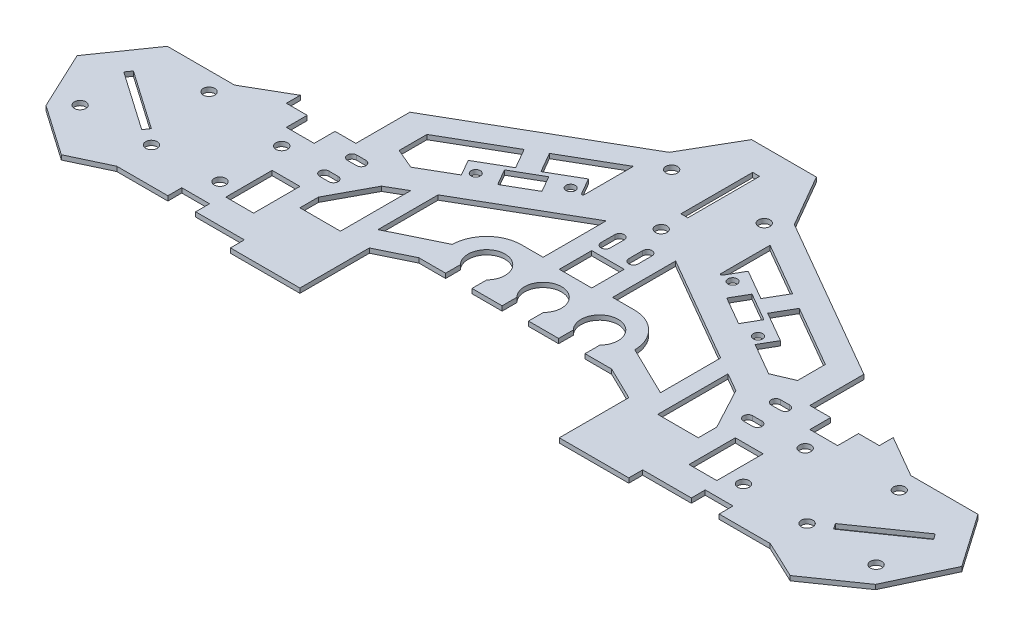
SolidWorks part; units mm, degrees
material "Thornel Mat VMA"
ref_plane "Alzado" through (0, 0, 0) normal (0, 0, 1) x (1, 0, 0)
ref_plane "Planta" through (0, 0, 0) normal (0, 1, 0) x (1, 0, 0)
ref_plane "Vista lateral" through (0, 0, 0) normal (1, 0, 0) x (0, 0, -1)
sketch "Croquis1" plane through (0, 0, 0) normal (0, 1, 0) x (1, 0, 0)
  line L0 (0, 0) -> (0, 58) construction
  line L1 (-7, 58) -> (7, 58)
  line L2 (7, 58) -> (13.5, 46.7417)
  line L3 (13.5, 46.7417) -> (49.007, 26.2417)
  line L4 (49.007, 26.2417) -> (49.007, 14.5814)
  line L5 (49.007, 14.5814) -> (53.507, 14.5814)
  line L6 (53.507, 14.5814) -> (53.507, 10.0814)
  line L7 (53.507, 10.0814) -> (59.507, 10.0814)
  line L8 (59.507, 10.0814) -> (59.507, 14.5814)
  line L9 (59.507, 14.5814) -> (64.007, 14.5814)
  line L10 (64.007, 14.5814) -> (64.007, 17.5814)
  line L11 (64.007, 17.5814) -> (73.007, 12.3853)
  line L12 (73.007, 12.3853) -> (87.507, 12.3853)
  line L13 (87.507, 12.3853) -> (95.5, 0.8912)
  line L14 (95.5, 0.8912) -> (89.5424, -11.7779)
  line L15 (89.5424, -11.7779) -> (78.6824, -19.3299)
  line L16 (78.6824, -19.3299) -> (70.538, -15.5)
  line L17 (70.538, -15.5) -> (59.507, -15.5)
  line L18 (59.507, -15.5) -> (59.507, -12.5)
  line L19 (59.507, -12.5) -> (53.507, -12.5)
  line L20 (53.507, -12.5) -> (53.507, -15.5)
  line L21 (53.507, -15.5) -> (43, -15.5)
  line L22 (43, -15.5) -> (43, -18.5)
  line L23 (43, -18.5) -> (28, -18.5)
  line L24 (28, -18.5) -> (28, -3.5)
  line L25 (28, -3.5) -> (20.8063, 0)
  line L26 (20.8063, 0) -> (15.05, 0)
  line L27 (15.05, 0) -> (15.05, 3.1933)
  line L28 (-2.85, 0) -> (-2.85, 3.1933)
  line L29 (9.35, 0) -> (9.35, 3.1933)
  line L30 (9.35, 0) -> (2.85, 0)
  line L31 (2.85, 0) -> (2.85, 3.1933)
  line L32 (-9.35, 0) -> (-2.85, 0)
  line L33 (-9.35, 0) -> (-9.35, 3.1933)
  line L34 (-15.05, 0) -> (-15.05, 3.1933)
  line L35 (-20.8063, 0) -> (-15.05, 0)
  line L36 (-28, -3.5) -> (-20.8063, 0)
  line L37 (-28, -18.5) -> (-28, -3.5)
  line L38 (-43, -18.5) -> (-28, -18.5)
  line L39 (-43, -15.5) -> (-43, -18.5)
  line L40 (-53.507, -15.5) -> (-43, -15.5)
  line L41 (-53.507, -12.5) -> (-53.507, -15.5)
  line L42 (-59.507, -12.5) -> (-53.507, -12.5)
  line L43 (-59.507, -15.5) -> (-59.507, -12.5)
  line L44 (-70.538, -15.5) -> (-59.507, -15.5)
  line L45 (-78.6824, -19.3299) -> (-70.538, -15.5)
  line L46 (-89.5424, -11.7779) -> (-78.6824, -19.3299)
  line L47 (-95.5, 0.8912) -> (-89.5424, -11.7779)
  line L48 (-87.507, 12.3853) -> (-95.5, 0.8912)
  line L49 (-73.007, 12.3853) -> (-87.507, 12.3853)
  line L50 (-64.007, 17.5814) -> (-73.007, 12.3853)
  line L51 (-64.007, 14.5814) -> (-64.007, 17.5814)
  line L52 (-59.507, 14.5814) -> (-64.007, 14.5814)
  line L53 (-59.507, 10.0814) -> (-59.507, 14.5814)
  line L54 (-53.507, 10.0814) -> (-59.507, 10.0814)
  line L55 (-53.507, 14.5814) -> (-53.507, 10.0814)
  line L56 (-49.007, 14.5814) -> (-53.507, 14.5814)
  line L57 (-49.007, 26.2417) -> (-49.007, 14.5814)
  line L58 (-13.5, 46.7417) -> (-49.007, 26.2417)
  line L59 (-7, 58) -> (-13.5, 46.7417)
  arc A0 (15.05, 3.1933) -> (9.35, 3.1933) centre (12.2, 6) ccw
  arc A1 (2.85, 3.1933) -> (-2.85, 3.1933) centre (0, 6) ccw
  arc A3 (-15.05, 3.1933) -> (-9.35, 3.1933) centre (-12.2, 6) cw
  point P54 (0, 10)
  dimension "D26" = 120
  dimension "D29" = 14
  dimension "D13" = 8
  dimension "D1" = 58
  dimension "D2" = 7
  dimension "D3" = 120
  dimension "D4" = 120
  dimension "D5" = 6
  dimension "D6" = 15
  dimension "D7" = 4.5
  dimension "D8" = 3
  dimension "D9" = 14.5
  dimension "D10" = 9
  dimension "D11" = 41
  dimension "D12" = 13
  dimension "D14" = 10
  dimension "D15" = 2.85
  dimension "D16" = 5.7
  dimension "D17" = 6.5
  dimension "D18" = 95.5
  dimension "D19" = 3
  dimension "D20" = 18.5
  dimension "D21" = 28
  dimension "D22" = 15
  dimension "D23" = 8
  dimension "D24" = 120
  dimension "D25" = 150
  dimension "D27" = 3
  dimension "D28" = 15
  dimension "D30" = 9
extrude "Saliente-Extruir1" add sketch "Croquis1" along normal blind 1
sketch "Croquis2" plane through (0, 1, 0) normal (0, 1, 0) x (1, 0, 0)
  line L0 (0, 10) -> (0, 58) construction
  line L1 (7, 58) -> (-7, 58) construction
  line L2 (3, 25.5) -> (3, 22.5) construction
  line L3 (-3.5, 20) -> (3.5, 20)
  line L4 (-3.5, 20) -> (-3.5, 13)
  line L5 (-3.5, 13) -> (3.5, 13)
  line L6 (3.5, 20) -> (3.5, 13)
  line L7 (-3.5, 20) -> (3.5, 13) construction
  line L8 (-3.5, 13) -> (3.5, 20) construction
  line L9 (-0.75, 52) -> (0.75, 52)
  line L10 (-0.75, 52) -> (-0.75, 36.5)
  line L11 (-0.75, 36.5) -> (0.75, 36.5)
  line L12 (0.75, 52) -> (0.75, 36.5)
  line L13 (-0.75, 52) -> (0.75, 36.5) construction
  line L14 (-0.75, 36.5) -> (0.75, 52) construction
  line L15 (4, 25.5) -> (4, 22.5)
  line L16 (2, 25.5) -> (2, 22.5)
  line L17 (34.25, -3.5) -> (43, -3.5)
  line L18 (43, -3.5) -> (43, 0.5)
  line L19 (43, 0.5) -> (38.25, 9.3582)
  line L20 (38.25, 9.3582) -> (34.25, 11.6676)
  line L21 (34.25, 11.6676) -> (34.25, -3.5)
  line L22 (43, -18.5) -> (43, -15.5) construction
  line L23 (43, -15.5) -> (53.507, -15.5) construction
  line L24 (47, 0.5) -> (53, 0.5)
  line L25 (47, 0.5) -> (47, -9.5)
  line L26 (47, -9.5) -> (53, -9.5)
  line L27 (53, 0.5) -> (53, -9.5)
  line L28 (-3, 25.5) -> (-3, 22.5) construction
  line L29 (-4, 25.5) -> (-4, 22.5)
  line L30 (-2, 25.5) -> (-2, 22.5)
  line L31 (-47, -9.5) -> (-53, -9.5)
  line L32 (-53, 0.5) -> (-53, -9.5)
  line L33 (-47, 0.5) -> (-53, 0.5)
  line L34 (-47, 0.5) -> (-47, -9.5)
  line L35 (-38.25, 9.3582) -> (-34.25, 11.6676)
  line L36 (-43, 0.5) -> (-38.25, 9.3582)
  line L37 (-43, -3.5) -> (-43, 0.5)
  line L38 (-34.25, -3.5) -> (-43, -3.5)
  line L39 (-34.25, 11.6676) -> (-34.25, -3.5)
  line L40 (49.007, 26.2417) -> (13.5, 46.7417) construction
  line L41 (95.5, 0.8912) -> (87.507, 12.3853) construction
  line L42 (91.5035, 6.6383) -> (59.5595, -15.5756) construction
  line L43 (73.8343, -4.7354) -> (86.5598, 4.1139)
  line L44 (73.8343, -4.7354) -> (74.6907, -5.9669)
  line L45 (86.5598, 4.1139) -> (87.4162, 2.8824)
  line L46 (74.6907, -5.9669) -> (87.4162, 2.8824)
  line L47 (73.8343, -4.7354) -> (87.4162, 2.8824) construction
  line L48 (86.5598, 4.1139) -> (74.6907, -5.9669) construction
  line L49 (-86.5598, 4.1139) -> (-87.4162, 2.8824)
  line L50 (-74.6907, -5.9669) -> (-87.4162, 2.8824)
  line L51 (-73.8343, -4.7354) -> (-74.6907, -5.9669)
  line L52 (-73.8343, -4.7354) -> (-86.5598, 4.1139)
  line L53 (44.75, 5.5) -> (46.75, 5.5) construction
  line L54 (44.75, 6.5) -> (46.75, 6.5)
  line L55 (44.75, 4.5) -> (46.75, 4.5)
  line L56 (44.75, 11.5) -> (46.75, 11.5) construction
  line L57 (44.75, 12.5) -> (46.75, 12.5)
  line L58 (44.75, 10.5) -> (46.75, 10.5)
  line L59 (47.75, 11.5) -> (47.75, 5.5) construction
  line L60 (-44.75, 11.5) -> (-46.75, 11.5) construction
  line L61 (-44.75, 12.5) -> (-46.75, 12.5)
  line L62 (-44.75, 10.5) -> (-46.75, 10.5)
  line L63 (-44.75, 5.5) -> (-46.75, 5.5) construction
  line L64 (-44.75, 6.5) -> (-46.75, 6.5)
  line L65 (-44.75, 4.5) -> (-46.75, 4.5)
  arc A0 (2.85, 3.1933) -> (-2.85, 3.1933) centre (0, 6) ccw construction
  arc A1 (4, 25.5) -> (2, 25.5) centre (3, 25.5) ccw
  arc A2 (2, 22.5) -> (4, 22.5) centre (3, 22.5) ccw
  arc A3 (-4, 25.5) -> (-2, 25.5) centre (-3, 25.5) cw
  arc A4 (-2, 22.5) -> (-4, 22.5) centre (-3, 22.5) cw
  arc A5 (44.75, 6.5) -> (44.75, 4.5) centre (44.75, 5.5) ccw
  arc A6 (46.75, 4.5) -> (46.75, 6.5) centre (46.75, 5.5) ccw
  arc A7 (44.75, 12.5) -> (44.75, 10.5) centre (44.75, 11.5) ccw
  arc A8 (46.75, 10.5) -> (46.75, 12.5) centre (46.75, 11.5) ccw
  arc A9 (-44.75, 12.5) -> (-44.75, 10.5) centre (-44.75, 11.5) cw
  arc A10 (-46.75, 10.5) -> (-46.75, 12.5) centre (-46.75, 11.5) cw
  arc A11 (-44.75, 6.5) -> (-44.75, 4.5) centre (-44.75, 5.5) cw
  arc A12 (-46.75, 4.5) -> (-46.75, 6.5) centre (-46.75, 5.5) cw
  point P7 (0, 16.5)
  point P12 (0, 44.25)
  point P19 (3, 24)
  point P24 (3, 21.5)
  point P25 (3, 26.5)
  point P44 (-3, 24)
  point P64 (80.6252, -0.9265)
  point P70 (45.75, 5.5)
  point P79 (47.75, 5.5)
  point P81 (45.75, 11.5)
  point P86 (47.75, 11.5)
  point P91 (-45.75, 11.5)
  point P98 (-45.75, 5.5)
  point P103 (0, 0)
  dimension "D6" = 1.5
  dimension "D1" = 7
  dimension "D2" = 3
  dimension "D3" = 15.5
  dimension "D4" = 1.5
  dimension "D5" = 6
  dimension "D7" = 4
  dimension "D8" = 2
  dimension "D9" = 5
  dimension "D10" = 8.75
  dimension "D11" = 20
  dimension "D12" = 4
  dimension "D13" = 5.5
  dimension "D14" = 10
  dimension "D15" = 6
  dimension "D16" = 4
  dimension "D17" = 6
  dimension "D18" = 1.5
  dimension "D19" = 15.5
  dimension "D20" = 2
  dimension "D21" = 4
  dimension "D22" = 4
  dimension "D23" = 13.5
  dimension "D24" = 4
extrude "Cortar-Extruir1" cut sketch "Croquis2" against normal blind 1
sketch "Croquis4" plane through (0, 1, 0) normal (0, 1, 0) x (1, 0, 0)
  line L0 (19.6993, 6.0989) -> (30.5, 0.8441)
  line L1 (30.5, 0.8441) -> (30.5, 13.8327)
  line L2 (30.5, 13.8327) -> (7.5, 27.1118)
  line L3 (7.5, 27.1118) -> (7.5, 13.5)
  line L4 (7.5, 13.5) -> (12.2, 13.5)
  line L5 (38.25, 9.3582) -> (34.25, 11.6676) construction
  line L6 (12.2, 10) -> (12.2, 13.5) construction
  line L7 (20.8063, 0) -> (28, -3.5) construction
  line L8 (34.25, 11.6676) -> (34.25, -3.5) construction
  line L11 (0, 0) -> (0, 58) construction
  line L12 (7, 58) -> (-7, 58) construction
  line L13 (-7.5, 13.5) -> (-12.2, 13.5)
  line L14 (-7.5, 27.1118) -> (-7.5, 13.5)
  line L15 (-30.5, 13.8327) -> (-7.5, 27.1118)
  line L16 (-30.5, 0.8441) -> (-30.5, 13.8327)
  line L17 (-19.6993, 6.0989) -> (-30.5, 0.8441)
  arc A0 (12.2, 13.5) -> (19.6993, 6.0989) centre (12.2, 6) cw
  arc A1 (15.05, 3.1933) -> (9.35, 3.1933) centre (12.2, 6) ccw construction
  arc A2 (-12.2, 13.5) -> (-19.6993, 6.0989) centre (-12.2, 6) ccw
  point P17 (34.25, 4.0838)
  point P30 (7.5, 25.9441)
  dimension "D1" = 23
  dimension "D2" = 3.5
  dimension "D3" = 5
  dimension "D4" = 3.75
extrude "Cortar-Extruir2" cut sketch "Croquis4" against normal blind 1
sketch "Croquis5" plane through (0, 1, 0) normal (0, 1, 0) x (1, 0, 0)
  line L0 (0, 36.5) -> (0, 20) construction
  line L1 (-0.75, 36.5) -> (0.75, 36.5) construction
  line L2 (3.5, 20) -> (-3.5, 20) construction
  line L3 (7, 58) -> (-7, 58) construction
  line L4 (21.9449, 29.1643) -> (28.007, 25.6643)
  line L6 (21.9449, 29.1643) -> (19.9449, 25.7002)
  line L7 (28.007, 25.6643) -> (26.007, 22.2002)
  line L8 (56.507, 10.0814) -> (56.507, 6.0814) construction
  line L9 (59.507, 10.0814) -> (53.507, 10.0814) construction
  line L14 (19.9449, 25.7002) -> (26.007, 22.2002)
  line L15 (21.9449, 29.1643) -> (26.007, 22.2002) construction
  line L20 (87.507, 12.3853) -> (73.007, 12.3853) construction
  line L21 (56.507, -12.5) -> (56.507, -7.25) construction
  line L22 (53.507, -12.5) -> (59.507, -12.5) construction
  line L23 (74.507, 8.3853) -> (85.9256, -8.0348) construction
  line L24 (95.5, 0.8912) -> (87.507, 12.3853) construction
  line L25 (91.5035, 6.6383) -> (71.7995, -7.064) construction
  line L26 (70.7732, -7.7776) -> (71.7995, -7.064) construction
  line L27 (28.007, 25.6643) -> (19.9449, 25.7002) construction
  line L28 (30.5, 13.8327) -> (7.5, 27.1118) construction
  line L29 (17.4808, 29.4323) -> (30.4711, 21.9323) construction
  line L30 (49.007, 14.5814) -> (49.007, 26.2417) construction
  line L31 (-28.007, 25.6643) -> (-26.007, 22.2002)
  line L32 (-19.9449, 25.7002) -> (-26.007, 22.2002)
  line L33 (-21.9449, 29.1643) -> (-19.9449, 25.7002)
  line L34 (-21.9449, 29.1643) -> (-28.007, 25.6643)
  circle A0 centre (10, 43.75) radius 1.25
  circle A1 centre (-10, 43.75) radius 1.25
  circle A2 centre (0, 31.5) radius 1.25
  circle A7 centre (56.507, 6.0814) radius 1.25
  circle A8 centre (-56.507, 6.0814) radius 1.25
  circle A9 centre (74.507, 8.3853) radius 1.25
  circle A10 centre (-74.507, 8.3853) radius 1.25
  circle A11 centre (56.507, -7.25) radius 1.25
  circle A12 centre (-56.507, -7.25) radius 1.25
  circle A13 centre (85.9256, -8.0348) radius 1.25
  circle A14 centre (70.7732, -7.7776) radius 1.25
  circle A15 centre (-85.9256, -8.0348) radius 1.25
  circle A16 centre (-70.7732, -7.7776) radius 1.25
  circle A17 centre (17.4808, 29.4323) radius 1
  circle A18 centre (30.4711, 21.9323) radius 1
  circle A19 centre (-30.4711, 21.9323) radius 1
  circle A20 centre (-17.4808, 29.4323) radius 1
  point P8 (10, 45)
  point P16 (23.976, 25.6823)
  point P21 (23.976, 25.6823)
  point P23 (22.2057, 24.9593)
  dimension "D1" = 2.5
  dimension "D4" = 4
  dimension "D9" = 15
  dimension "D10" = 2
  dimension "D11" = 5.25
  dimension "D14" = 21
  dimension "D15" = 20
  dimension "D2" = 13
  dimension "D3" = 10
  dimension "D5" = 5
  dimension "D6" = 5
  dimension "D7" = 4
  dimension "D8" = 7
  dimension "D12" = 4
  dimension "D13" = 18
  dimension "D16" = 24
extrude "Cortar-Extruir3" cut sketch "Croquis5" against normal blind 10
sketch "Croquis7" plane through (0, 1, 0) normal (0, 1, 0) x (1, 0, 0)
  line L0 (14.75, 29.6355) -> (14.75, 40.2465)
  line L1 (14.75, 40.2465) -> (26.2439, 33.6105)
  line L2 (26.2439, 33.6105) -> (23.7439, 29.2803)
  line L3 (23.7439, 29.2803) -> (17.2487, 33.0303)
  line L4 (17.2487, 33.0303) -> (15.2165, 29.5105)
  line L5 (29.708, 31.6105) -> (43.007, 23.9323)
  line L6 (43.007, 23.9323) -> (43.007, 17.9323)
  line L7 (43.007, 17.9323) -> (38.6314, 16.0662)
  line L8 (38.6314, 16.0662) -> (31.7032, 20.0662)
  line L9 (31.7032, 20.0662) -> (33.7032, 23.5303)
  line L10 (33.7032, 23.5303) -> (27.208, 27.2803)
  line L11 (27.208, 27.2803) -> (29.708, 31.6105)
  line L12 (0.75, 36.5) -> (0.75, 52) construction
  line L13 (49.007, 14.5814) -> (49.007, 26.2417) construction
  line L14 (49.007, 26.2417) -> (13.5, 46.7417) construction
  line L15 (0, 36.5) -> (0, 20) construction
  line L16 (28.007, 25.6643) -> (21.9449, 29.1643) construction
  line L17 (-0.75, 36.5) -> (0.75, 36.5) construction
  line L18 (3.5, 20) -> (-3.5, 20) construction
  line L19 (-27.208, 27.2803) -> (-29.708, 31.6105)
  line L20 (38.25, 9.3582) -> (34.25, 11.6676) construction
  line L21 (26.007, 22.2002) -> (28.007, 25.6643) construction
  line L22 (21.9449, 29.1643) -> (19.9449, 25.7002) construction
  line L23 (24.976, 27.4143) -> (30.476, 36.9406) construction
  line L24 (-33.7032, 23.5303) -> (-27.208, 27.2803)
  line L25 (-31.7032, 20.0662) -> (-33.7032, 23.5303)
  line L26 (-38.6314, 16.0662) -> (-31.7032, 20.0662)
  line L27 (-43.007, 17.9323) -> (-38.6314, 16.0662)
  line L28 (-43.007, 23.9323) -> (-43.007, 17.9323)
  line L29 (-29.708, 31.6105) -> (-43.007, 23.9323)
  line L30 (-17.2487, 33.0303) -> (-15.2165, 29.5105)
  line L31 (-23.7439, 29.2803) -> (-17.2487, 33.0303)
  line L32 (-26.2439, 33.6105) -> (-23.7439, 29.2803)
  line L33 (-14.75, 40.2465) -> (-26.2439, 33.6105)
  line L34 (-14.75, 29.6355) -> (-14.75, 40.2465)
  arc A0 (14.75, 29.6355) -> (15.2165, 29.5105) centre (15, 29.6355) ccw
  arc A1 (-14.75, 29.6355) -> (-15.2165, 29.5105) centre (-15, 29.6355) cw
  dimension "D12" = 0.25
  dimension "D1" = 14
  dimension "D2" = 6
  dimension "D3" = 1
  dimension "D4" = 5
  dimension "D5" = 6
  dimension "D6" = 6
  dimension "D7" = 6
  dimension "D8" = 4
  dimension "D9" = 2
  dimension "D10" = 6
  dimension "D11" = 8
extrude "Cortar-Extruir4" cut sketch "Croquis7" against normal through all
